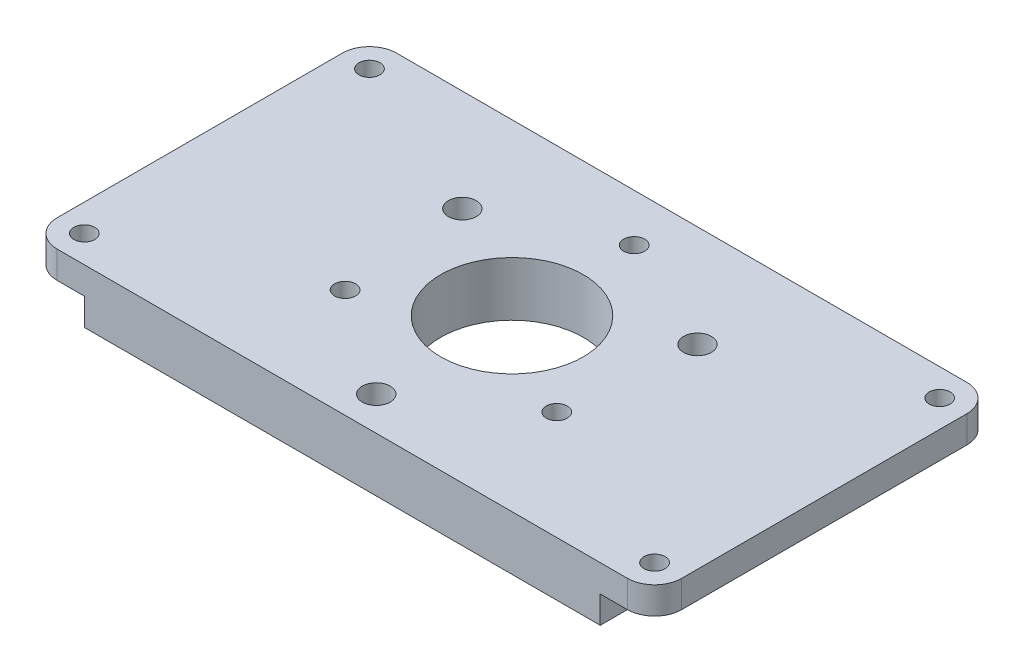
SolidWorks part; units mm, degrees
material "6061 合金"
ref_plane "前视基准面" through (0, 0, 0) normal (0, 0, 1) x (1, 0, 0)
ref_plane "上视基准面" through (0, 0, 0) normal (0, 1, 0) x (1, 0, 0)
ref_plane "右视基准面" through (0, 0, 0) normal (1, 0, 0) x (0, 0, -1)
sketch "草图1" plane through (0, 0, 0) normal (0, 1, 0) x (1, 0, 0)
  line L0 (0, 0) -> (0, -73.9322) construction
  line L1 (-46, -25) -> (46, -25)
  line L2 (-46, -25) -> (-46, 25)
  line L3 (-46, 25) -> (46, 25)
  line L4 (46, -25) -> (46, 25)
  line L5 (-46, -25) -> (46, 25) construction
  line L6 (-46, 25) -> (46, -25) construction
  line L7 (0, 0) -> (-84.9414, 0) construction
  circle A0 centre (-42, -21) radius 1.55
  circle A1 centre (0, 0) radius 10.5
  circle A2 centre (0, -20) radius 2.05
  circle A3 centre (-17.3205, 10) radius 2.05
  circle A4 centre (17.3205, 10) radius 2.05
  circle A5 centre (42, -21) radius 1.55
  circle A6 centre (42, 21) radius 1.55
  circle A7 centre (-42, 21) radius 1.55
  circle A8 centre (0, 18) radius 1.55
  circle A9 centre (15.5885, -9) radius 1.55
  circle A10 centre (-15.5885, -9) radius 1.55
  point P0 (0, 0)
  point P20 (0, 0)
  point P33 (0, 0)
  dimension "D3" = 3.1
  dimension "D5" = 4
  dimension "D6" = 4.1
  dimension "D7" = 20
  dimension "D9" = 21
  dimension "D10" = 3.1
  dimension "D11" = 18
  dimension "D1" = 92
  dimension "D2" = 50
  dimension "D4" = 4
  dimension "D8" = 3
  dimension "D12" = 3
extrude "凸台-拉伸1" add sketch "草图1" against normal mid plane 8
sketch "草图13" plane through (0, -4, 0) normal (0, -1, 0) x (1, 0, 0)
  line L0 (46, -25) -> (-46, -25) construction
  line L1 (46, 25) -> (38, 25)
  line L2 (46, 25) -> (46, -25)
  line L3 (46, -25) -> (38, -25)
  line L4 (38, 25) -> (38, -25)
  line L5 (0, 0) -> (0, -43.6333) construction
  line L6 (-46, 25) -> (-38, 25)
  line L7 (-46, 25) -> (-46, -25)
  line L8 (-46, -25) -> (-38, -25)
  line L9 (-38, 25) -> (-38, -25)
  dimension "D1" = 8
extrude "切除-拉伸8" cut sketch "草图13" against normal offset from surface (4 mm away) 4 up to face at (-15.5885, 4, 10.55)
fillet "Fillet2" radius 4 4 edges at (-46, 2, 25) (-46, 2, -25) (46, 2, 25) (46, 2, -25)
sketch "Sketch1" plane through (0, -4, 0) normal (0, -1, 0) x (-1, 0, 0)
  circle A0 centre (0, 18) radius 6
  circle A1 centre (15.5885, -9) radius 6
  circle A2 centre (-15.5885, -9) radius 6
  point P10 (0, 0)
  dimension "D1" = 12
extrude "Cut-Extrude1" cut sketch "Sketch1" against normal blind 5
sketch "Sketch3" plane through (0, -4, 0) normal (0, -1, 0) x (1, 0, 0)
  line L0 (38, -25) -> (-38, -25) construction
  line L1 (-1.5877, -15.25) -> (-3.1754, -18)
  line L2 (-3.1754, -18) -> (-1.5877, -20.75)
  line L3 (-1.5877, -20.75) -> (1.5877, -20.75)
  line L4 (1.5877, -20.75) -> (3.1754, -18)
  line L5 (3.1754, -18) -> (1.5877, -15.25)
  line L6 (1.5877, -15.25) -> (-1.5877, -15.25)
  line L7 (-14.0007, 6.25) -> (-12.413, 9)
  line L8 (-17.1762, 6.25) -> (-14.0007, 6.25)
  line L9 (-18.7639, 9) -> (-17.1762, 6.25)
  line L10 (-17.1762, 11.75) -> (-18.7639, 9)
  line L11 (-14.0007, 11.75) -> (-17.1762, 11.75)
  line L12 (-12.413, 9) -> (-14.0007, 11.75)
  line L13 (12.413, 9) -> (14.0007, 6.25)
  line L14 (14.0007, 11.75) -> (12.413, 9)
  line L15 (17.1762, 11.75) -> (14.0007, 11.75)
  line L16 (18.7639, 9) -> (17.1762, 11.75)
  line L17 (17.1762, 6.25) -> (18.7639, 9)
  line L18 (14.0007, 6.25) -> (17.1762, 6.25)
  circle A0 centre (0, -18) radius 2.75 construction
  point P26 (0, 0)
  dimension "D1" = 5.5
extrude "Cut-Extrude2" [suppressed] cut sketch "Sketch3" against normal blind 5
